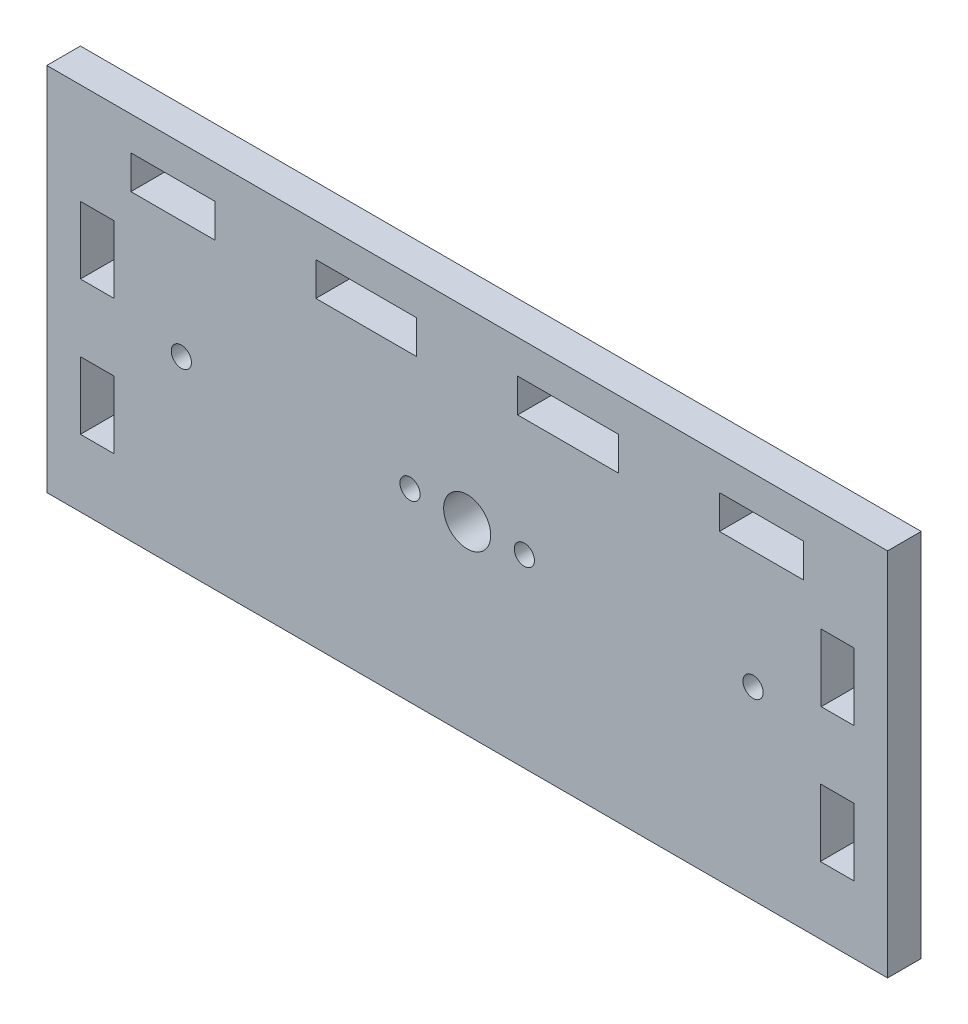
SolidWorks part; units mm, degrees
ref_plane "Plan de face" through (0, 0, 0) normal (0, 0, 1) x (1, 0, 0)
ref_plane "Plan de dessus" through (0, 0, 0) normal (0, 1, 0) x (1, 0, 0)
ref_plane "Plan de droite" through (0, 0, 0) normal (1, 0, 0) x (0, 0, -1)
sketch "Esquisse1" plane through (0, 0, 0) normal (0, 0, 1) x (1, 0, 0)
  line L0 (-66.6112, 37.3798) -> (58.3888, -17.6202) construction
  line L1 (58.3888, -17.6202) -> (-66.6112, -17.6202)
  line L2 (58.3888, -17.6202) -> (58.3888, 37.3798)
  line L3 (58.3888, 37.3798) -> (-66.6112, 37.3798)
  line L4 (-66.6112, -17.6202) -> (-66.6112, 37.3798)
  line L5 (58.3888, 37.3798) -> (-66.6112, -17.6202) construction
  dimension "D1" = 125
  dimension "D2" = 55
extrude "Boss.-Extru.3" add sketch "Esquisse1" along normal blind 5
sketch "Esquisse2" plane through (0, 0, 5) normal (0, 0, 1) x (1, 0, 0)
  line L0 (-66.6112, 37.3798) -> (58.3888, -17.6202) construction
  line L1 (58.3888, -17.6202) -> (58.3888, 37.3798) construction
  line L2 (58.3888, 37.3798) -> (-66.6112, -17.6202) construction
  line L3 (58.3888, 37.3798) -> (-66.6112, 37.3798) construction
  circle A0 centre (-4.1112, 9.8798) radius 3.5
  dimension "D1" = 7
extrude "Enlèv. mat.-Extru.1" cut sketch "Esquisse2" against normal blind 5
sketch "Esquisse3" plane through (0, 0, 5) normal (0, 0, 1) x (1, 0, 0)
  line L0 (58.3888, -17.6202) -> (58.3888, 37.3798) construction
  line L1 (53.3888, 22.3798) -> (48.5204, 22.3798)
  line L2 (53.3888, 22.3798) -> (53.3888, 12.3798)
  line L3 (53.3888, 12.3798) -> (48.5204, 12.3798)
  line L4 (48.5204, 22.3798) -> (48.5204, 12.3798)
  line L5 (58.3888, 37.3798) -> (-66.6112, 37.3798) construction
  line L6 (-66.6112, 37.3798) -> (-66.6112, -17.6202) construction
  line L7 (53.3888, 2.3798) -> (48.3888, 2.3798)
  line L8 (53.3888, 2.3798) -> (53.3888, -7.6202)
  line L9 (53.3888, -7.6202) -> (48.3888, -7.6202)
  line L10 (48.3888, 2.3798) -> (48.3888, -7.6202)
  line L11 (-56.6112, 22.3798) -> (-61.6112, 22.3798)
  line L12 (-56.6112, 22.3798) -> (-56.6112, 12.3798)
  line L13 (-56.6112, 12.3798) -> (-61.6112, 12.3798)
  line L14 (-61.6112, 22.3798) -> (-61.6112, 12.3798)
  line L15 (-66.6112, 37.3798) -> (-66.6112, -17.6202) construction
  line L16 (-56.6112, 2.3798) -> (-61.6112, 2.3798)
  line L17 (-56.6112, 2.3798) -> (-56.6112, -7.6202)
  line L18 (-56.6112, -7.6202) -> (-61.6112, -7.6202)
  line L19 (-61.6112, 2.3798) -> (-61.6112, -7.6202)
  line L20 (-54.1112, 32.3798) -> (-41.6112, 32.3798)
  line L21 (-54.1112, 32.3798) -> (-54.1112, 27.3798)
  line L22 (-54.1112, 27.3798) -> (-41.6112, 27.3798)
  line L23 (-41.6112, 32.3798) -> (-41.6112, 27.3798)
  line L25 (-26.6112, 32.3798) -> (-11.6112, 32.3798)
  line L26 (-26.6112, 32.3798) -> (-26.6112, 27.3798)
  line L27 (-26.6112, 27.3798) -> (-11.6112, 27.3798)
  line L28 (-11.6112, 32.3798) -> (-11.6112, 27.3798)
  line L29 (3.3888, 32.3798) -> (18.3888, 32.3798)
  line L30 (3.3888, 32.3798) -> (3.3888, 27.3798)
  line L31 (3.3888, 27.3798) -> (18.3888, 27.3798)
  line L32 (18.3888, 32.3798) -> (18.3888, 27.3798)
  line L33 (33.3888, 32.3798) -> (45.8888, 32.3798)
  line L34 (33.3888, 32.3798) -> (33.3888, 27.3798)
  line L35 (33.3888, 27.3798) -> (45.8888, 27.3798)
  line L36 (45.8888, 32.3798) -> (45.8888, 27.3798)
  dimension "D1" = 10
  dimension "D2" = 4.8684
  dimension "D3" = 5
  dimension "D4" = 15
  dimension "D5" = 10
  dimension "D6" = 5
  dimension "D7" = 5
  dimension "D8" = 10
  dimension "D9" = 15
  dimension "D10" = 10
  dimension "D11" = 5
  dimension "D12" = 5
  dimension "D13" = 5
  dimension "D14" = 10
  dimension "D15" = 5
  dimension "D16" = 12.5
  dimension "D17" = 5
  dimension "D18" = 12.5
  dimension "D19" = 5
  dimension "D20" = 15
  dimension "D21" = 15
  dimension "D22" = 5
  dimension "D23" = 5
  dimension "D24" = 15
  dimension "D25" = 15
  dimension "D26" = 12.5
  dimension "D27" = 15
  dimension "D28" = 10
extrude "Enlèv. mat.-Extru.2" cut sketch "Esquisse3" against normal blind 5 contours L12 L13 L14 L11 | L10 L9 L8 L7 | L4 L3 L2 L1 | L17 L18 L19 L16 | L27 L28 L25 L26 | L22 L23 L20 L21 | L35 L36 L33 L34 | L31 L32 L29 L30
sketch "Esquisse4" plane through (0, 0, 5) normal (0, 0, 1) x (1, 0, 0)
  line L0 (-66.6112, 37.3798) -> (-66.6112, -17.6202) construction
  line L4 (58.3888, 37.3798) -> (-66.6112, 37.3798) construction
  circle A0 centre (-46.6112, 9.8798) radius 1.5
  circle A1 centre (38.3888, 9.8798) radius 1.5
  dimension "D1" = 3
  dimension "D4" = 3
  dimension "D2" = 20
  dimension "D3" = 27.5
  dimension "D5" = 27.5
extrude "Enlèv. mat.-Extru.3" cut sketch "Esquisse4" against normal blind 2.5
sketch "Esquisse5" plane through (0, 0, 5) normal (0, 0, 1) x (1, 0, 0)
  line L0 (58.3888, 37.3798) -> (-66.6112, 37.3798) construction
  circle A0 centre (4.3888, 9.8798) radius 1.5
  circle A1 centre (-12.6112, 9.8798) radius 1.5
  circle A2 centre (-4.1112, 9.8798) radius 3.5 construction
  dimension "D2" = 8.5
  dimension "D3" = 3
  dimension "D4" = 3
  dimension "D5" = 27.5
  dimension "D6" = 27.5
  dimension "D1" = 17
extrude "Enlèv. mat.-Extru.4" cut sketch "Esquisse5" against normal through all
